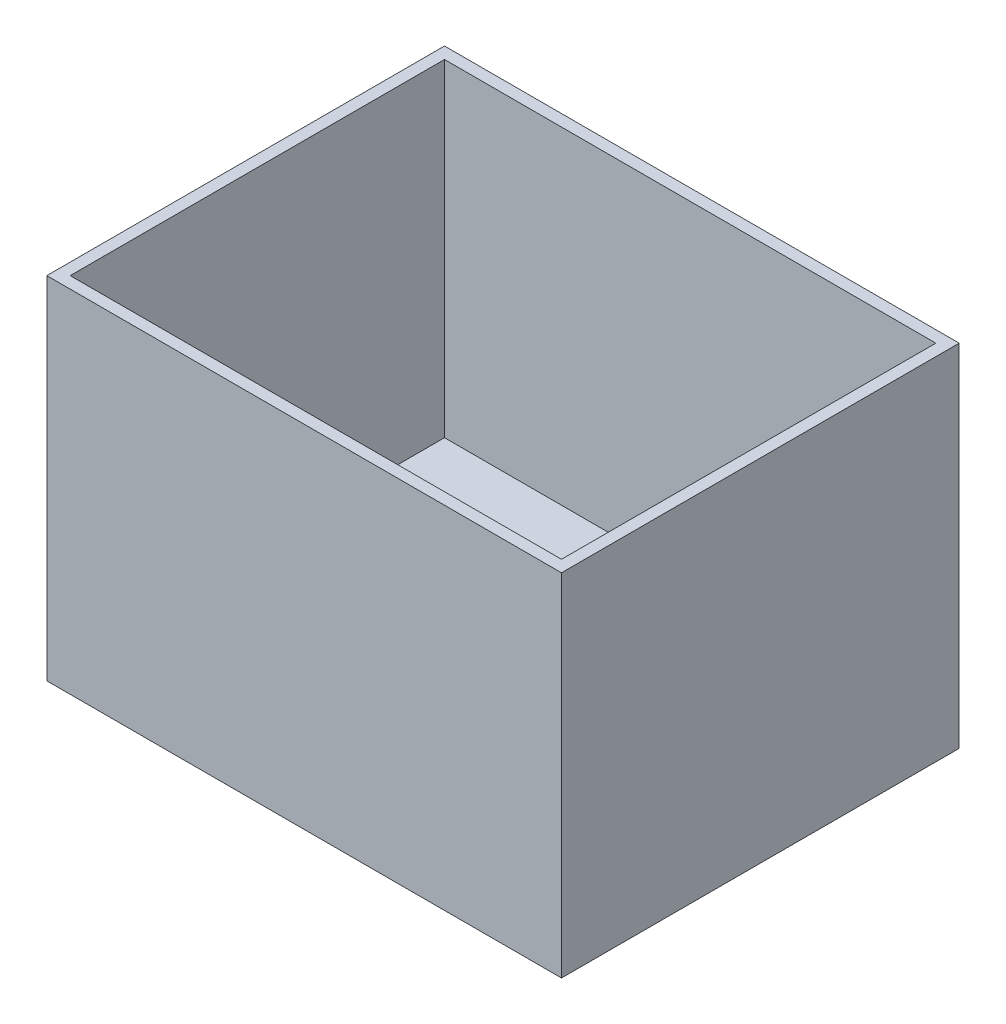
SolidWorks part; units mm, degrees
ref_plane "Front Plane" through (0, 0, 0) normal (0, 0, 1) x (1, 0, 0)
ref_plane "Top Plane" through (0, 0, 0) normal (0, 1, 0) x (1, 0, 0)
ref_plane "Right Plane" through (0, 0, 0) normal (1, 0, 0) x (0, 0, -1)
sketch "Sketch2" plane through (0, 0, 0) normal (0, 1, 0) x (1, 0, 0)
  line L1 (-220, -170) -> (220, -170)
  line L2 (-220, -170) -> (-220, 170)
  line L3 (-220, 170) -> (220, 170)
  line L4 (220, -170) -> (220, 170)
  line L5 (-220, -170) -> (220, 170) construction
  line L6 (-220, 170) -> (220, -170) construction
  point P0 (0, 0)
  dimension "D1" = 440
  dimension "D2" = 340
extrude "Boss-Extrude1" add sketch "Sketch2" along normal blind 300
sketch "Sketch3" plane through (0, 300, 0) normal (0, 1, 0) x (1, 0, 0)
  line L1 (-210, -160) -> (210, -160)
  line L2 (-210, -160) -> (-210, 160)
  line L3 (-210, 160) -> (210, 160)
  line L4 (210, -160) -> (210, 160)
  line L5 (-210, -160) -> (210, 160) construction
  line L6 (-210, 160) -> (210, -160) construction
  point P0 (0, 0)
  dimension "D1" = 320
  dimension "D2" = 420
extrude "Cut-Extrude1" cut sketch "Sketch3" against normal blind 280
